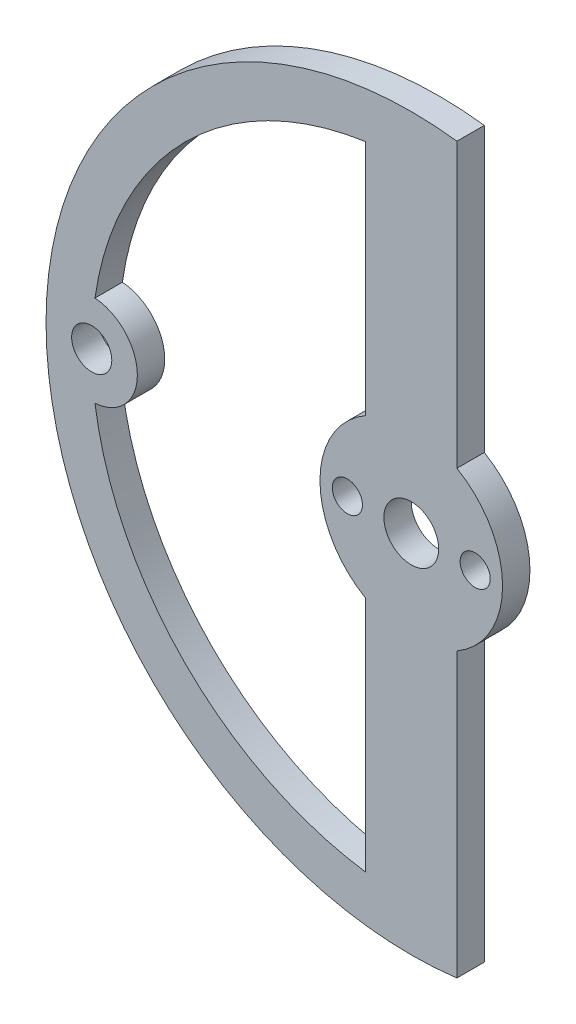
SolidWorks part; units mm, degrees
ref_plane "Front Plane" through (0, 0, 0) normal (0, 0, 1) x (1, 0, 0)
ref_plane "Top Plane" through (0, 0, 0) normal (0, 1, 0) x (1, 0, 0)
ref_plane "Right Plane" through (0, 0, 0) normal (1, 0, 0) x (0, 0, -1)
sketch "Sketch1" plane through (0, 0, 0) normal (0, 0, 1) x (1, 0, 0)
  line L0 (0, 40) -> (0, -40) construction
  line L1 (-5, -35) -> (5, -35)
  line L2 (-5, -35) -> (-5, 35)
  line L3 (-5, 35) -> (5, 35)
  line L4 (5, -35) -> (5, 35)
  line L5 (-5, -35) -> (5, 35) construction
  line L6 (-5, 35) -> (5, -35) construction
  circle A0 centre (0, 0) radius 40
  circle A1 centre (0, 0) radius 3
  circle A2 centre (7, 0) radius 1.65
  circle A3 centre (-7, 0) radius 1.65
  circle A4 centre (-35, 0) radius 2.2
  circle A5 centre (0, 0) radius 10
  arc A8 (-34.6429, -4.9872) -> (-34.6429, 4.9872) centre (-35, 0) ccw
  arc A9 (-34.6429, -4.9872) -> (-34.6429, 4.9872) centre (0, 0) ccw
  dimension "D1" = 80
  dimension "D2" = 6
  dimension "D3" = 3.3
  dimension "D5" = 3.3
  dimension "D7" = 4.4
  dimension "D9" = 20
  dimension "D10" = 35
  dimension "D11" = 5
  dimension "D12" = 70
  dimension "D4" = 7
  dimension "D6" = 7
  dimension "D8" = 35
  dimension "D13" = 10
extrude "Boss-Extrude1" add sketch "Sketch1" along normal blind 3 contours A0 A9 L2 L3 L4 L1 A8 A4 | L4 A9 L2 A5 | L4 A5 L2 A1 | L4 A5 A2 | L2 A5 A3 | L2 A9 L4 A5 | A9 L2 L1 | A9 L1 L4 | A9 L3 L2 | A9 L4 L3
sketch "Sketch3" plane through (0, 0, 3) normal (0, 0, 1) x (1, 0, 0)
  line L0 (5, 39.6863) -> (5, 8.6603)
  line L1 (5, 8.6603) -> (14.2891, 8.6603)
  line L2 (14.2891, 8.6603) -> (14.2891, -8.6603)
  line L3 (14.2891, -8.6603) -> (5, -8.6603)
  line L4 (5, -8.6603) -> (5, -39.6863)
  line L5 (5, -39.6863) -> (45, -39.6863)
  line L6 (45, -39.6863) -> (45, 39.6863)
  line L7 (45, 39.6863) -> (5, 39.6863)
  circle A0 centre (0, 0) radius 40 construction
  dimension "D1" = 9.2891
  dimension "D2" = 40
extrude "Cut-Extrude1" cut sketch "Sketch3" against normal blind 10
